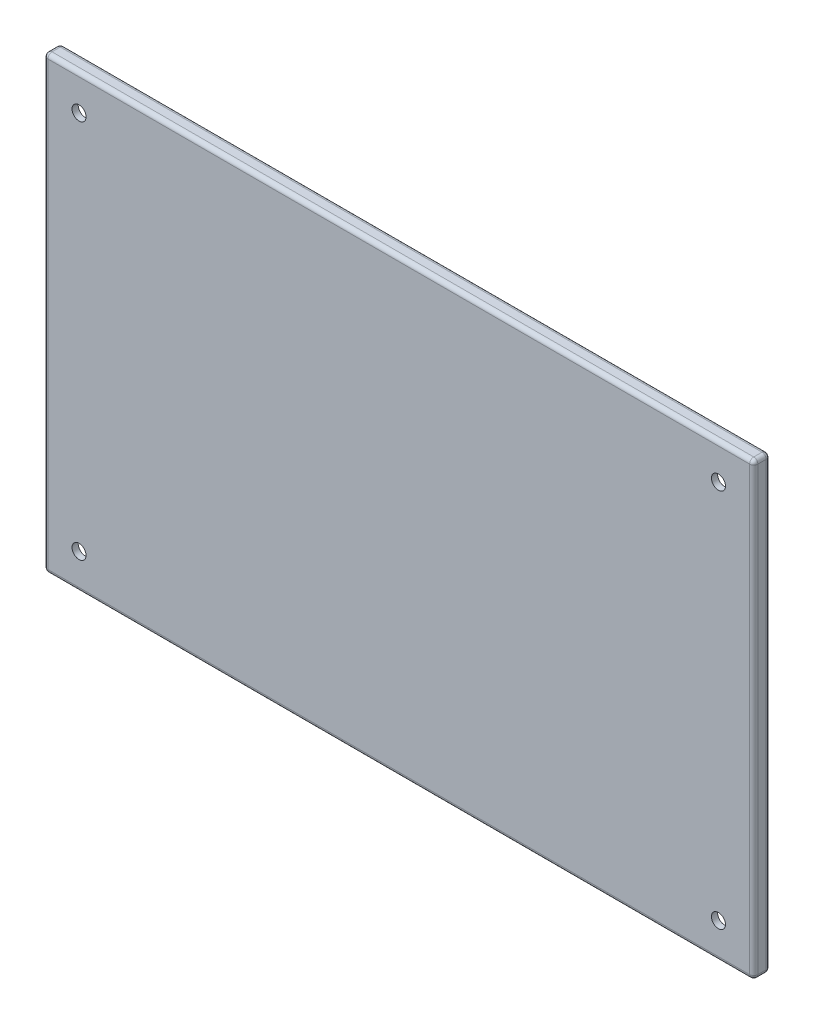
SolidWorks part; units mm, degrees
ref_plane "Front Plane" through (0, 0, 0) normal (0, 0, 1) x (1, 0, 0)
ref_plane "Top Plane" through (0, 0, 0) normal (0, 1, 0) x (1, 0, 0)
ref_plane "Right Plane" through (0, 0, 0) normal (1, 0, 0) x (0, 0, -1)
sketch "Sketch1" plane through (0, 0, 0) normal (0, 0, 1) x (1, 0, 0)
  line L0 (-82.5, 0) -> (82.5, 0) construction
  line L1 (82.5, -51.05) -> (-82.5, -51.05)
  line L2 (82.5, -51.05) -> (82.5, 51.05)
  line L3 (82.5, 51.05) -> (-82.5, 51.05)
  line L4 (-82.5, -51.05) -> (-82.5, 51.05)
  line L5 (82.5, -51.05) -> (-82.5, 51.05) construction
  line L6 (82.5, 51.05) -> (-82.5, -51.05) construction
  line L7 (0, 51.05) -> (0, -51.05) construction
  circle A0 centre (-77.45, 46) radius 1.7
  circle A1 centre (77.45, 46) radius 1.7
  circle A2 centre (77.45, -46) radius 1.7
  circle A3 centre (-77.45, -46) radius 1.7
  point P0 (0, 0)
  dimension "D3" = 3.4
  dimension "D4" = 5.05
  dimension "D5" = 5.05
  dimension "D1" = 102.1
  dimension "D2" = 165
extrude "Boss-Extrude1" add sketch "Sketch1" along normal blind 1.5
sketch "Sketch2" plane through (0, 0, 1.5) normal (0, 0, 1) x (1, 0, 0)
  line L1 (-82.5, 51.05) -> (82.5, 51.05)
  line L2 (-82.5, 51.05) -> (-82.5, -51.05)
  line L3 (-82.5, -51.05) -> (82.5, -51.05)
  line L4 (82.5, 51.05) -> (82.5, -51.05)
  line L5 (-86, 54.55) -> (86, 54.55)
  line L6 (-86, 54.55) -> (-86, -54.55)
  line L7 (-86, -54.55) -> (86, -54.55)
  line L8 (86, 54.55) -> (86, -54.55)
  dimension "D1" = 3.5
  dimension "D2" = 3.5
  dimension "D3" = 3.5
  dimension "D4" = 3.5
extrude "Boss-Extrude2" add sketch "Sketch2" against normal blind 4
sketch "Sketch3" plane through (0, 0, -2.5) normal (0, 0, -1) x (-1, 0, 0)
  line L0 (82.5, 51.05) -> (82.5, -51.05) construction
  line L1 (-82.5, 51.05) -> (82.5, 51.05)
  line L2 (-82.5, 51.05) -> (-82.5, 52.05)
  line L3 (-82.5, 52.05) -> (82.5, 52.05)
  line L4 (82.5, 51.05) -> (82.5, 52.05)
  dimension "D1" = 1
extrude "Cut-Extrude1" cut sketch "Sketch3" against normal up to surface (2.5 mm away) up to face at (0, 0, 0)
fillet "Fillet1" radius 1 12 edges at (-86, 0, -2.5) (-86, 0, 1.5) (0, -54.55, -2.5) (-86, -54.55, -0.5) (0, -54.55, 1.5) (86, 0, -2.5) (86, -54.55, -0.5) (86, 0, 1.5) (-86, 54.55, -0.5) (0, 54.55, -2.5) (86, 54.55, -0.5) (0, 54.55, 1.5)
